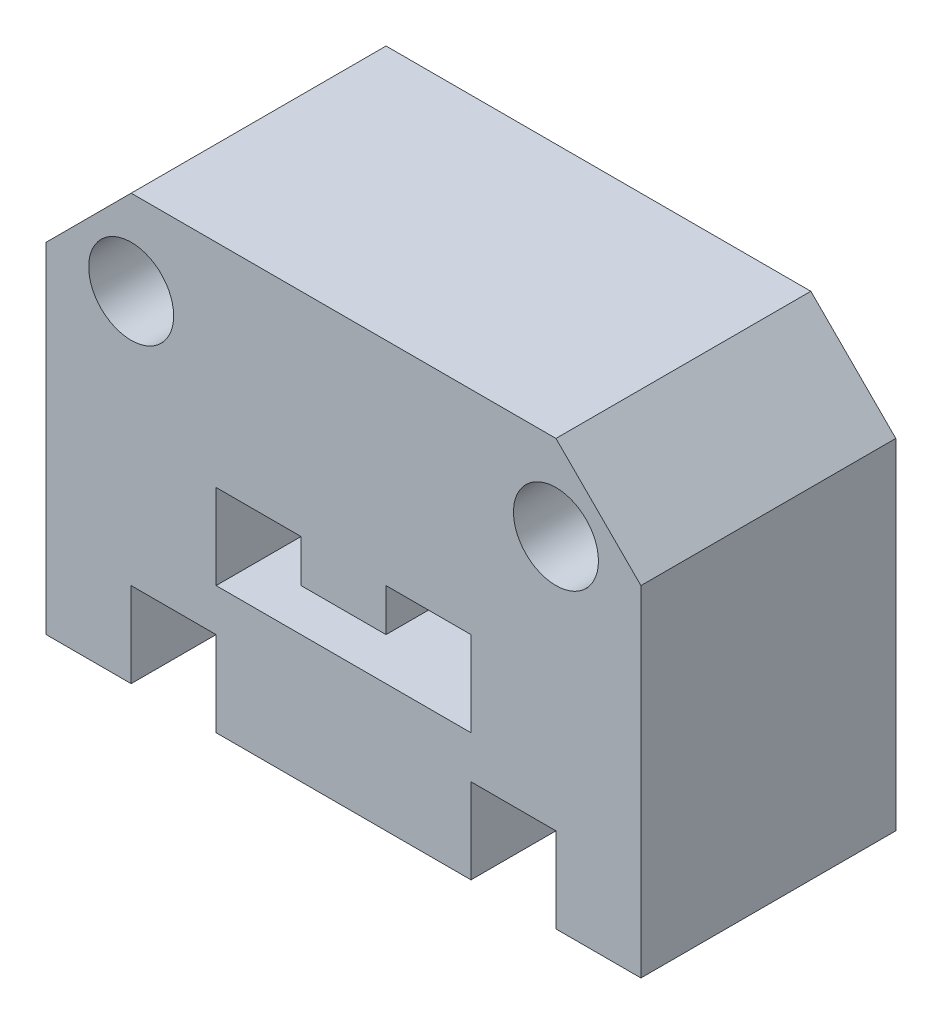
SolidWorks part; units mm, degrees
ref_plane "Front Plane" through (0, 0, 0) normal (0, 0, 1) x (1, 0, 0)
ref_plane "Top Plane" through (0, 0, 0) normal (0, 1, 0) x (1, 0, 0)
ref_plane "Right Plane" through (0, 0, 0) normal (1, 0, 0) x (0, 0, -1)
sketch "Sketch1" plane through (0, 0, 0) normal (0, 0, 1) x (1, 0, 0)
  line L0 (0, 0) -> (0, -21573.2393) construction
  line L1 (0, 0) -> (21573.2393, 0) construction
  line L2 (-35, 40) -> (-25, 50)
  line L3 (-25, 50) -> (25, 50)
  line L4 (-35, 40) -> (-35, 0)
  line L5 (-35, 0) -> (-25, 0)
  line L6 (35, 40) -> (35, 0)
  line L7 (25, 50) -> (35, 40)
  line L8 (-25, 0) -> (-25, 10)
  line L9 (-25, 10) -> (-15, 10)
  line L10 (-15, 10) -> (-15, 0)
  line L11 (15, 10) -> (15, 0)
  line L12 (25, 10) -> (15, 10)
  line L13 (25, 0) -> (25, 10)
  line L14 (-15, 0) -> (15, 0)
  line L15 (25, 0) -> (35, 0)
  line L16 (-5, 25) -> (-5, 20)
  line L17 (-15, 15) -> (15, 15)
  line L18 (-15, 15) -> (-15, 25)
  line L19 (-15, 25) -> (-5, 25)
  line L20 (15, 15) -> (15, 25)
  line L21 (-5, 20) -> (5, 20)
  line L22 (5, 20) -> (5, 25)
  line L23 (5, 25) -> (15, 25)
  circle A0 centre (-25, 40) radius 5
  circle A1 centre (25, 40) radius 5
  point P5 (-35, 50)
  point P8 (35, 50)
  point P30 (15, 20)
  point P34 (0, 0)
  point P35 (0, 0)
  dimension "D11" = 10
  dimension "D1" = 70
  dimension "D2" = 50
  dimension "D3" = 10
  dimension "D4" = 45
  dimension "D5" = 10
  dimension "D6" = 45
  dimension "D7" = 10
  dimension "D8" = 10
  dimension "D9" = 15
  dimension "D10" = 10
extrude "Boss-Extrude1" add sketch "Sketch1" along normal mid plane 30
